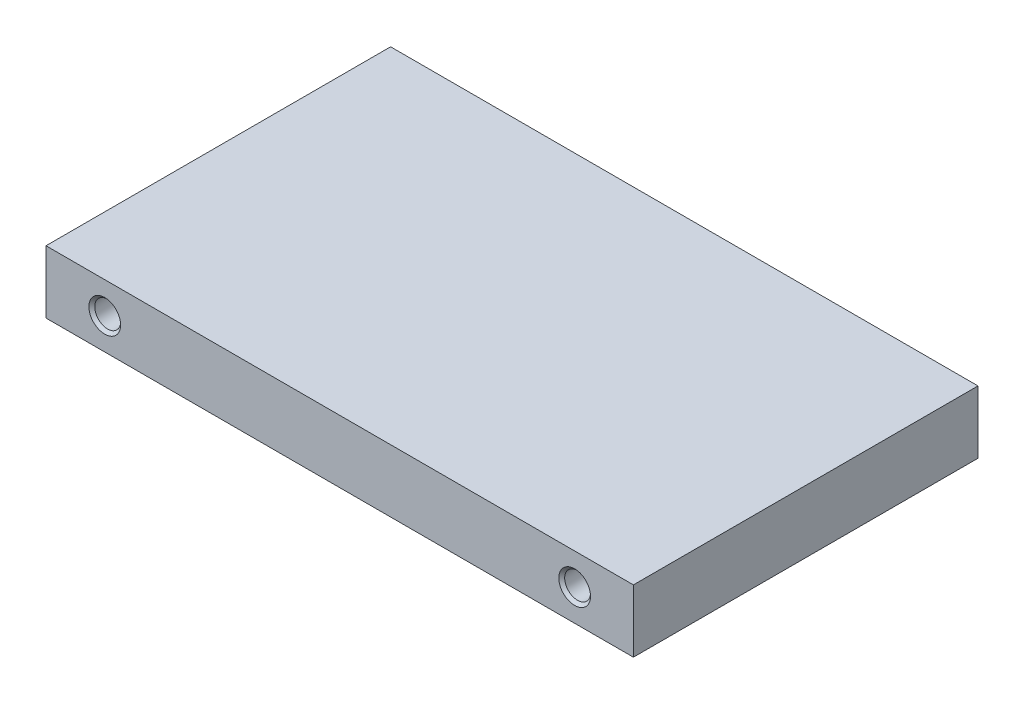
SolidWorks part; units mm, degrees
ref_plane "Front Plane" through (0, 0, 0) normal (0, 0, 1) x (1, 0, 0)
ref_plane "Top Plane" through (0, 0, 0) normal (0, 1, 0) x (1, 0, 0)
ref_plane "Right Plane" through (0, 0, 0) normal (1, 0, 0) x (0, 0, -1)
sketch "Sketch1" plane through (0, 0, 0) normal (0, 1, 0) x (1, 0, 0)
  line L0 (0, 36.6879) -> (0, -28.1994) construction
  line L1 (-61.4863, 0) -> (107.6964, 0) construction
  line L2 (-57.3704, 14) -> (83.1751, 14) construction
  line L3 (-53.5, 22) -> (81.5, 22) construction
  line L4 (-53.5, 22) -> (-53.5, -22) construction
  line L5 (-53.5, -22) -> (81.5, -22) construction
  line L6 (81.5, 22) -> (81.5, -22) construction
  line L7 (14, 38.4145) -> (14, -23.4375) construction
  line L8 (21.5, 22) -> (-53.5, 22)
  line L9 (-53.5, 22) -> (-53.5, -22)
  line L10 (-53.5, -22) -> (21.5, -22)
  line L11 (21.5, -22) -> (21.5, 22)
  dimension "D1" = 135
  dimension "D2" = 67.5
  dimension "D3" = 14
  dimension "D4" = 44
  dimension "D5" = 14
  dimension "D6" = 22
  dimension "D7" = 75
extrude "Boss-Extrude2" add sketch "Sketch1" along normal blind 8 contours L8 L9 L10 L11
sketch "Sketch2" plane through (0, 0, 22) normal (0, 0, 1) x (1, 0, 0)
  line L0 (-59.1737, 4) -> (45.5182, 4) construction
  line L1 (0, 12.4542) -> (0, -6.7626) construction
  line L2 (-57.252, 0) -> (44.941, 0) construction
  point P7 (-46, 4)
  point P8 (14, 4)
  dimension "D1" = 4
  dimension "D4" = 60
  dimension "D2" = 14
hole_wizard "M4x0.7 Tapped Hole2" positions "Sketch16" profile "Sketch18" tap size "M4x0.7" standard "ANSI Metric" end condition through all
sketch "Sketch16" plane through (0, 0, 22) normal (0, 0, 1) x (1, 0, 0)
  point P0 (-46, 4)
  point P3 (14, 4)
sketch "Sketch18" plane through (-46, 4, 22) normal (1, 0, 0) x (0, -1, 0)
  line L0 (0, 0) -> (0, 44)
  line L1 (0, 44) -> (1.65, 44)
  line L2 (1.65, 44) -> (1.65, 0.375)
  line L3 (1.65, 0.375) -> (2.025, 0)
  line L5 (2.025, 0) -> (0, 0)
  line L6 (-1.65, 0.375) -> (-2.025, 0) construction
  line L11 (0, -6.35) -> (0, 107.95) construction
  dimension "Thru Tap Drill Dia." = 3.3
  dimension "Thru Tap Drill Depth" = 44
  dimension "Near C'Sink Dia." = 4.05
  dimension "Near C'Sink Angle" = 90
cosmetic thread "Hole Thread1" parameters "D2"=4
cosmetic thread "Hole Thread2" parameters "D2"=4
equation "\"plateD_length\"= 75"
equation "\"plateC_length\"=135"
equation "\"D1@Sketch1\"=\"plateC_length\""
equation "\"D2@Sketch1\"=\"plateC_length\"/2"
equation "\"plateD_offsetX\"=14"
equation "\"D3@Sketch1\"=\"plateD_offsetX\""
equation "\"plateD_height\"=60"
equation "\"plateD_width\"=44"
equation "\"D4@Sketch1\"=\"plateD_width\""
equation "\"plateD_offset\"=12"
equation "\"plateD_offsetY\"=12"
equation "\"plateD_offsetZ\"=14"
equation "\"D5@Sketch1\"=\"plateD_offsetZ\""
equation "\"D6@Sketch1\"=\"plateD_width\"/2"
equation "\"plateD_thickness\"=8"
equation "\"D1\" = \"plateD_thickness\""
equation "\"D7@Sketch1\"=\"plateD_length\""
equation "\"D1@Boss-Extrude2\"=\"plateD_thickness\""
equation "\"D1@Sketch2\"=\"plateD_thickness\"/2"
equation "\"plateD_bolt_spacing\"=60"
equation "\"D4@Sketch2\"=\"plateD_bolt_spacing\""
equation "\"plateD_bolt_pattern_offsetX\"=16"
equation "\"D2@Sketch2\"=\"plateD_offsetX\""
